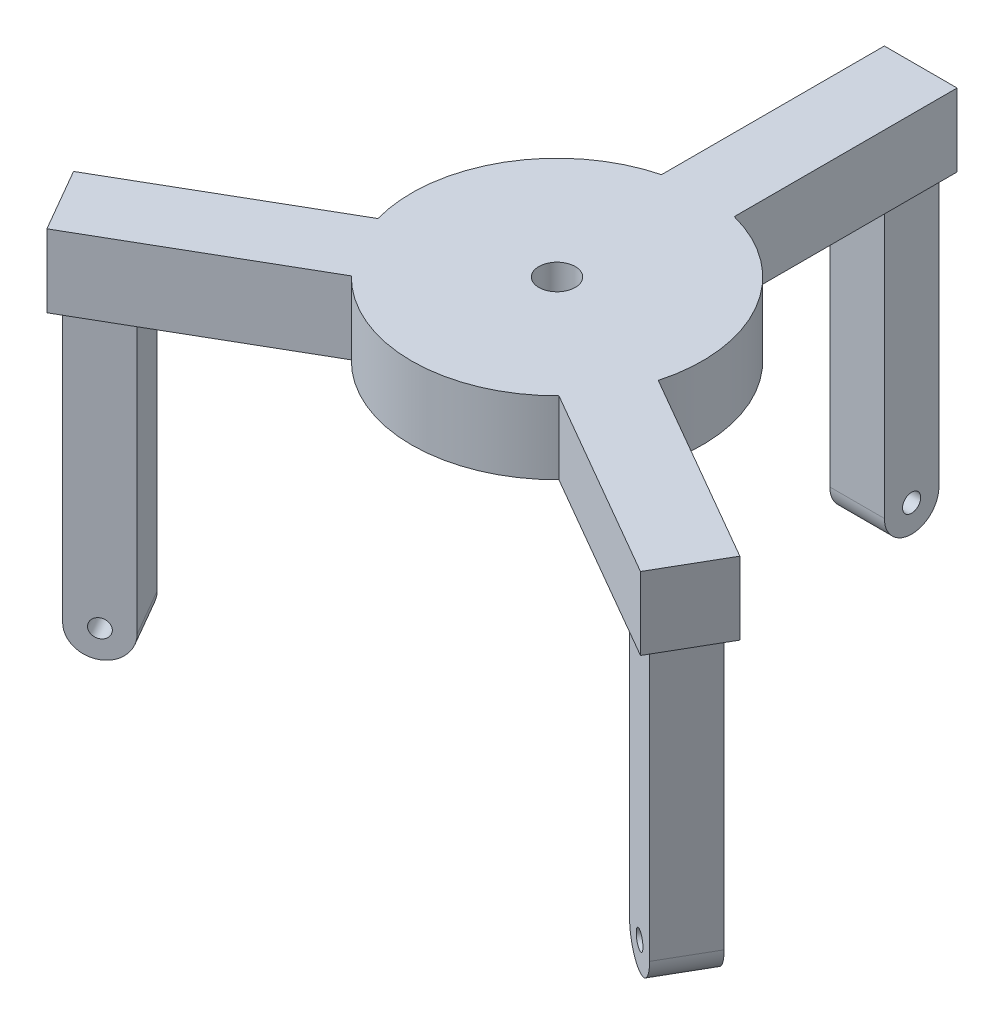
SolidWorks part; units mm, degrees
material "AISI 1020"
ref_plane "Front Plane" through (0, 0, 0) normal (0, 0, 1) x (1, 0, 0)
ref_plane "Top Plane" through (0, 0, 0) normal (0, 1, 0) x (1, 0, 0)
ref_plane "Right Plane" through (0, 0, 0) normal (1, 0, 0) x (0, 0, -1)
sketch "Sketch1" plane through (0, 0, 0) normal (0, 1, 0) x (1, 0, 0)
  line L0 (0, 0) -> (0, 200) construction
  line L1 (163.2051, -117.3205) -> (183.2051, -82.6795)
  line L2 (20, 200) -> (-20, 200)
  line L3 (20, 200) -> (20, 77.4597)
  line L4 (163.2051, -117.3205) -> (57.082, -56.0503)
  line L5 (-20, 200) -> (-20, 77.4597)
  line L6 (183.2051, -82.6795) -> (77.082, -21.4093)
  line L7 (0, 0) -> (173.2051, -100) construction
  line L8 (-183.2051, -82.6795) -> (-163.2051, -117.3205)
  line L9 (-183.2051, -82.6795) -> (-77.082, -21.4093)
  line L10 (-163.2051, -117.3205) -> (-57.082, -56.0503)
  line L11 (0, 0) -> (-173.2051, -100) construction
  circle A0 centre (0, 0) radius 80
  point P22 (0, 0)
  dimension "D1" = 160
  dimension "D3" = 200
  dimension "D4" = 40
  dimension "D5" = 20
  dimension "D6" = 3
extrude "Boss-Extrude1" add sketch "Sketch1" along normal blind 40
sketch "Sketch2" plane through (0, 0, 0) normal (0, -1, 0) x (1, 0, 0)
  line L0 (0, -200) -> (0, -180) construction
  line L2 (20, -200) -> (-20, -200) construction
  line L4 (15, -195) -> (-15, -195)
  line L5 (15, -195) -> (15, -165)
  line L6 (15, -165) -> (-15, -165)
  line L7 (-15, -195) -> (-15, -165)
  line L8 (15, -195) -> (-15, -165) construction
  line L9 (15, -165) -> (-15, -195) construction
  dimension "D1" = 20
  dimension "D2" = 30
  dimension "D3" = 30
extrude "Boss-Extrude2" add sketch "Sketch2" along normal blind 150
sketch "Sketch3" plane through (15, 0, 0) normal (1, 0, 0) x (0, 0, -1)
  line L0 (165, -150) -> (195, -150)
  arc A0 (165, -150) -> (195, -150) centre (180, -150) ccw
extrude "Boss-Extrude4" add sketch "Sketch3" against normal blind 30
sketch "Sketch5" plane through (15, 0, 0) normal (1, 0, 0) x (0, 0, -1)
  line L0 (195, -150) -> (165, -150) construction
  circle A0 centre (180, -150) radius 5
  dimension "D1" = 10
extrude "Cut-Extrude2" cut sketch "Sketch5" against normal blind 30
pattern_circular "CirPattern1" count 3 every 120 about axis through (0, 0, 0) along (0, 1, 0) of "Boss-Extrude2", "Boss-Extrude4"
sketch "Sketch6" plane through (0, 40, 0) normal (0, 1, 0) x (1, 0, 0)
  circle A0 centre (0, 0) radius 10
  dimension "D1" = 20
extrude "Cut-Extrude3" cut sketch "Sketch6" against normal blind 50
sketch "Sketch7" plane through (7.5, 0, 12.9904) normal (0.5, 0, 0.866) x (0.866, 0, -0.5)
  line L0 (-165, -150) -> (-195, -150) construction
  circle A0 centre (-180, -150) radius 5
  dimension "D1" = 10
extrude "Cut-Extrude4" cut sketch "Sketch7" against normal blind 30
sketch "Sketch8" plane through (-7.5, 0, 12.9904) normal (-0.5, 0, 0.866) x (0.866, 0, 0.5)
  line L0 (195, -150) -> (165, -150) construction
  circle A0 centre (180, -150) radius 5
  dimension "D1" = 10
extrude "Cut-Extrude5" cut sketch "Sketch8" against normal blind 30
